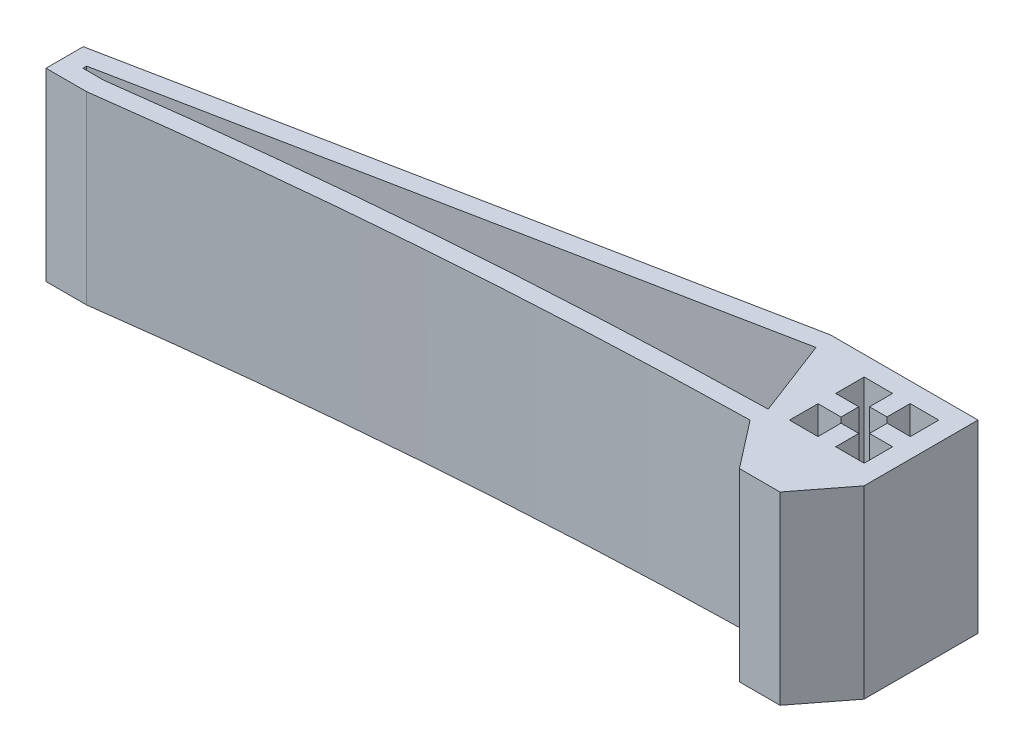
SolidWorks part; units mm, degrees
ref_plane "Plan de face" through (0, 0, 0) normal (0, 0, 1) x (1, 0, 0)
ref_plane "Plan de dessus" through (0, 0, 0) normal (0, 1, 0) x (1, 0, 0)
ref_plane "Plan de droite" through (0, 0, 0) normal (1, 0, 0) x (0, 0, -1)
sketch "Esquisse1" plane through (0, 0, 0) normal (0, 1, 0) x (1, 0, 0)
  line L0 (-15.4191, 0) -> (15.4191, 0) construction
  line L7 (0, 15.4191) -> (0, -15.4191) construction
  line L8 (-9.8036, -9.8036) -> (10.1964, 10.1964) construction
  line L9 (-9.8036, -2.3036) -> (-9.8036, -9.8036) construction
  line L10 (-9.8036, -2.3036) -> (-8.4647, -2.3036) construction
  line L11 (-8.4647, -2.3036) -> (-8.4647, -6.0358) construction
  line L12 (-7.6111, -6.3893) -> (-3.7147, -2.4929) construction
  line L13 (-6.5505, -7.45) -> (-2.654, -3.5536) construction
  line L14 (-2.4647, -8.3036) -> (-6.1969, -8.3036) construction
  line L15 (-2.4647, -9.8036) -> (-2.4647, -8.3036) construction
  line L16 (-2.4647, -9.8036) -> (-9.8036, -9.8036) construction
  line L17 (-2.5353, 10.1964) -> (-2.5353, 8.6964) construction
  line L18 (-2.5353, 10.1964) -> (-10.0353, 10.1964) construction
  line L19 (-10.0353, 2.6964) -> (-10.0353, 10.1964) construction
  line L20 (-10.0353, 2.6964) -> (-8.4647, 2.6964) construction
  line L21 (-8.4647, 2.6964) -> (-8.4647, 6.4287) construction
  line L22 (-7.6111, 6.7822) -> (-3.7147, 2.8858) construction
  line L23 (-6.6211, 7.8429) -> (-2.7247, 3.9464) construction
  line L24 (-2.5353, 8.6964) -> (-6.2676, 8.6964) construction
  line L25 (10.0353, 2.6964) -> (8.5353, 2.6964) construction
  line L26 (10.0353, 2.6964) -> (10.1964, 10.1964) construction
  line L27 (2.5353, 10.1964) -> (10.1964, 10.1964) construction
  line L28 (2.5353, 10.1964) -> (2.5353, 8.6964) construction
  line L29 (2.5353, 8.6964) -> (6.2676, 8.6964) construction
  line L30 (6.6211, 7.8429) -> (2.7247, 3.9464) construction
  line L31 (7.6818, 6.7822) -> (3.7853, 2.8858) construction
  line L32 (8.5353, 2.6964) -> (8.5353, 6.4287) construction
  line L33 (2.4647, -9.8036) -> (2.4647, -8.3036) construction
  line L34 (2.4647, -9.8036) -> (10.1964, -9.8036) construction
  line L35 (10.0353, -2.3036) -> (10.1964, -9.8036) construction
  line L36 (10.0353, -2.3036) -> (8.5353, -2.3036) construction
  line L37 (8.5353, -2.3036) -> (8.5353, -6.0358) construction
  line L38 (7.6818, -6.3893) -> (3.7853, -2.4929) construction
  line L39 (6.6211, -7.45) -> (2.7247, -3.5536) construction
  line L40 (2.4647, -8.3036) -> (6.2676, -8.3036) construction
  line L41 (-3.7147, 2.8858) -> (-3.7147, -2.4929) construction
  line L42 (-2.654, -3.5536) -> (2.7247, -3.5536) construction
  line L43 (-2.7247, 3.9464) -> (2.7247, 3.9464) construction
  line L44 (3.7853, 2.8858) -> (3.7853, -2.4929) construction
  line L63 (-10.0736, 10.1) -> (-2.3736, 10.1)
  line L65 (15.4191, -15.4191) -> (15.4191, 15.4191)
  line L66 (15.4191, 15.4191) -> (-15.4191, 15.4191)
  line L68 (15.4191, -15.4191) -> (-15.4191, 15.4191) construction
  line L69 (15.4191, 15.4191) -> (-15.4191, -15.4191) construction
  line L70 (-2.3736, 10.1) -> (-2.3736, 3.85)
  line L71 (-2.3736, 3.85) -> (2.3736, 3.85)
  line L72 (2.3736, 3.85) -> (2.3736, 10.1)
  line L73 (2.3736, 10.1) -> (10.1264, 10.1)
  line L74 (10.1264, 10.1) -> (10.1264, 2.4)
  line L75 (10.1264, 2.4) -> (3.8764, 2.4)
  line L76 (3.8764, -2.4) -> (3.8764, 2.4)
  line L77 (10.1264, -2.4) -> (3.8764, -2.4)
  line L78 (10.1264, -10.1) -> (10.1264, -2.4)
  line L79 (2.4264, -10.1) -> (10.1264, -10.1)
  line L80 (2.4264, -3.85) -> (2.4264, -10.1)
  line L81 (-2.3736, -3.85) -> (2.4264, -3.85)
  line L82 (-2.3736, -10.1) -> (-2.3736, -3.85)
  line L83 (-10.0736, -10.1) -> (-2.3736, -10.1)
  line L84 (-10.0736, -2.4) -> (-10.0736, -10.1)
  line L85 (-3.8236, -2.4) -> (-10.0736, -2.4)
  line L86 (-3.8236, 2.4) -> (-3.8236, -2.4)
  line L87 (-10.0736, 2.4) -> (-3.8236, 2.4)
  line L88 (-10.0736, 2.4) -> (-10.0736, 10.1)
  line L90 (-182.1851, -28.2346) -> (-193.1602, -28.2346)
  line L94 (-5.4875, -28.2346) -> (5.4875, -28.2346)
  line L95 (5.4875, -28.2346) -> (15.4191, -15.4191)
  line L96 (-5.4875, -28.2346) -> (-15.4191, -15.4191)
  line L97 (-193.1602, -28.2346) -> (-193.1602, -18.1382)
  line L99 (-15.4191, 15.4191) -> (-24.4944, 15.4191)
  line L100 (-24.4944, 15.4191) -> (-193.1602, -18.1382)
  line L101 (-23.5188, 10.5152) -> (-188.1602, -22.2414)
  line L102 (-188.1602, -23.2346) -> (-188.1602, -22.2414)
  line L103 (-182.5189, -23.2346) -> (-188.1602, -23.2346)
  line L104 (-15.5187, -10.4201) -> (-23.5188, 10.5152)
  arc A0 (-8.4647, 6.4287) -> (-7.6111, 6.7822) centre (-7.9647, 6.4287) cw construction
  arc A1 (-8.4647, -6.0358) -> (-7.6111, -6.3893) centre (-7.9647, -6.0358) ccw construction
  arc A2 (-6.5505, -7.45) -> (-6.1969, -8.3036) centre (-6.1969, -7.8036) ccw construction
  arc A3 (6.6211, -7.45) -> (6.2676, -8.3036) centre (6.2676, -7.8036) cw construction
  arc A4 (8.5353, -6.0358) -> (7.6818, -6.3893) centre (8.0353, -6.0358) cw construction
  arc A5 (7.6818, 6.7822) -> (8.5353, 6.4287) centre (8.0353, 6.4287) cw construction
  arc A6 (6.2676, 8.6964) -> (6.6211, 7.8429) centre (6.2676, 8.1964) cw construction
  arc A7 (-6.6211, 7.8429) -> (-6.2676, 8.6964) centre (-6.2676, 8.1964) cw construction
  spline S0 degree 2 poles (-182.1851, -28.2346) (-99.136, -17.0866) (-15.4191, -15.4191) knots 0 0 0 1 1 1
  spline S1 degree 1 poles (-182.5189, -23.2346) (-15.5187, -10.4201) knots 0 0 1 1 construction
  spline S2 degree 2 poles (-182.5189, -23.2346) (-99.3528, -12.0899) (-15.5187, -10.4201) knots 0.001988 0.001988 0.001988 1 1 1
  point P1 (-3.8236, 0)
  point P2 (0, 3.85)
  point P11 (-2.4647, -9.0536)
  point P12 (2.4647, -9.0536)
  point P54 (0, 0)
  point P67 (0, 0)
  point P93 (0, -28.2346)
  point P104 (0, 0)
  dimension "D8" = 0.5
  dimension "D1" = 5
  dimension "D3" = 20
  dimension "D5" = 7.5
  dimension "D6" = 1.5
  dimension "D7" = 1.5
extrude "Boss.-Extru.1" add sketch "Esquisse1" along normal blind 50
